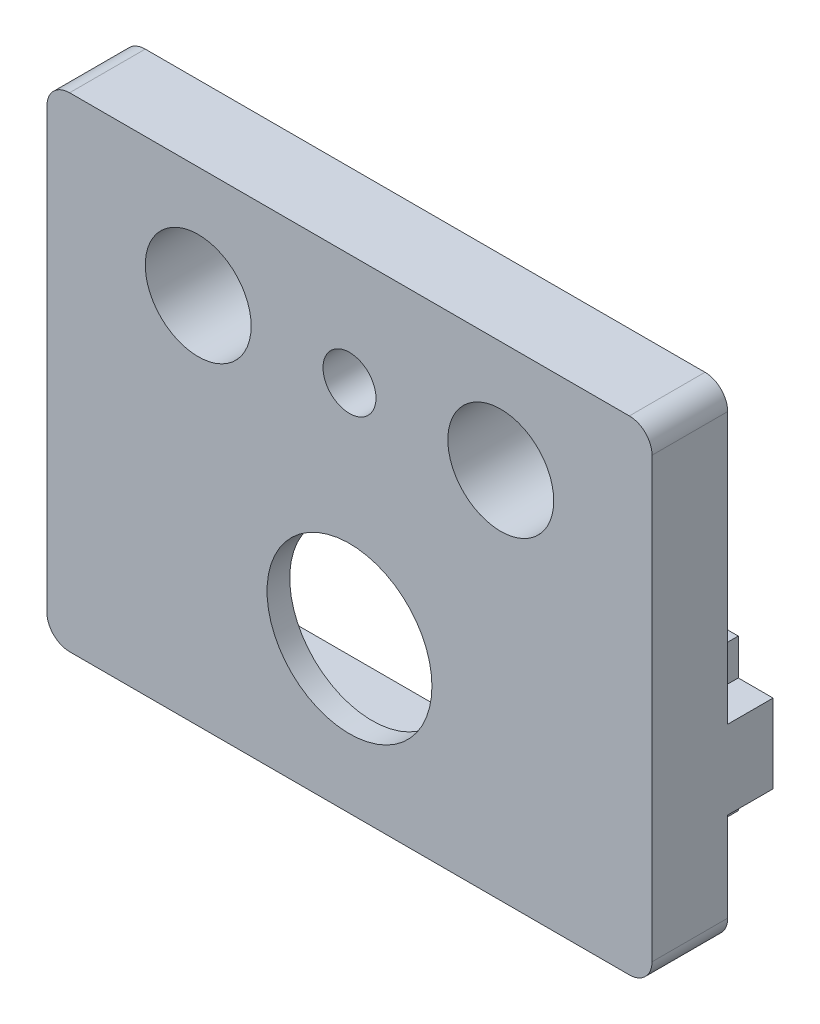
SolidWorks part; units mm, degrees
ref_plane "前视基准面" through (0, 0, 0) normal (0, 0, 1) x (1, 0, 0)
ref_plane "上视基准面" through (0, 0, 0) normal (0, 1, 0) x (1, 0, 0)
ref_plane "右视基准面" through (0, 0, 0) normal (1, 0, 0) x (0, 0, -1)
sketch "草图1" plane through (0, 0, 0) normal (0, 0, 1) x (1, 0, 0)
  line L1 (-9.5, -5.75) -> (9.5, -5.75)
  line L3 (-9.5, 5.75) -> (9.5, 5.75)
  line L5 (-20, -10) -> (20, -10)
  line L6 (-20, -10) -> (-20, 10)
  line L11 (-20, 10) -> (20, 10)
  line L12 (20, -10) -> (20, 10)
  line L13 (-20, -10) -> (20, 10) construction
  line L14 (-20, 10) -> (20, -10) construction
  arc A0 (9.5, -5.75) -> (9.5, 5.75) centre (-0.7708, 0) ccw
  arc A1 (-9.5, -5.75) -> (-9.5, 5.75) centre (0.7708, 0) cw
  point P0 (0, 0)
  point P6 (0, 0)
  point P7 (0, 0)
extrude "凸台-拉伸1" add sketch "草图1" along normal blind 3.5
sketch "草图2" plane through (0, 0, 3.5) normal (0, 0, 1) x (1, 0, 0)
  line L4 (20, -10) -> (20, 10)
  line L5 (20, 10) -> (-20, 10)
  line L6 (-20, 10) -> (-20, -10)
  line L7 (-20, -10) -> (20, -10)
  line L8 (20, -10) -> (20, 10)
  line L9 (20, 10) -> (-20, 10)
  line L10 (-20, 10) -> (-20, -10)
  line L11 (-20, -10) -> (20, -10)
  circle A0 centre (0, 0) radius 5.25
  dimension "D1" = 0
extrude "凸台-拉伸2" add sketch "草图2" along normal blind 1.5
sketch "草图3" plane through (0, 0, 5) normal (0, 0, 1) x (1, 0, 0)
  line L9 (-16.5607, 5.5) -> (-18.2, 5.5)
  line L13 (-13.9, -2.8393) -> (-13.9, 2.8393)
  line L19 (-16.5607, 5.5) -> (-13.9, 2.8393)
  line L22 (-18.2, 3.1) -> (-18.2, 5.5)
  line L23 (-18.2, 3.1) -> (-20, 3.1)
  line L24 (-18.2, -3.1) -> (-20, -3.1)
  line L25 (-18.2, -3.1) -> (-18.2, -5.5)
  line L28 (-16.5607, -5.5) -> (-13.9, -2.8393)
  line L32 (-16.5607, -5.5) -> (-18.2, -5.5)
  line L41 (18.2, 3.1) -> (20, 3.1)
  line L45 (18.2, 3.1) -> (18.2, 5.5)
  line L48 (16.5607, 5.5) -> (13.9, 2.8393)
  line L54 (13.9, -2.8393) -> (13.9, 2.8393)
  line L56 (16.5607, 5.5) -> (18.2, 5.5)
  line L63 (16.5607, -5.5) -> (18.2, -5.5)
  line L67 (16.5607, -5.5) -> (13.9, -2.8393)
  line L70 (18.2, -3.1) -> (18.2, -5.5)
  line L74 (18.2, -3.1) -> (20, -3.1)
  line L88 (-20, 3.1) -> (-20, -3.1)
  line L90 (20, 3.1) -> (20, -3.1)
  point P0 (-10, 0)
  point P8 (-10, 8.2)
  point P9 (-9.8043, 8.2)
  point P13 (-10, 8.2)
  point P20 (-5, 5)
  point P33 (-15, 5)
  point P50 (-15, -5)
  point P51 (-5, -5)
  point P52 (-10, -8.2)
  point P53 (-9.8043, -8.2)
  point P54 (10, 0)
  point P58 (10, 8.2)
  point P59 (10.1957, 8.2)
  point P63 (10, 8.2)
  point P70 (15, 5)
  point P83 (5, 5)
  point P102 (5, -5)
  point P103 (15, -5)
  point P104 (10, -8.2)
  point P105 (10.1957, -8.2)
extrude "凸台-拉伸3" add sketch "草图3" against normal blind 8
sketch "草图4" plane through (0, 0, 5) normal (0, 0, 1) x (1, 0, 0)
  line L3 (-20, 10) -> (-20, -10) construction
  line L6 (20, 10) -> (-20, 10)
  line L8 (-20, 10) -> (-20, 22)
  line L9 (-20, 22) -> (20, 22)
  line L10 (20, 22) -> (20, 10)
  circle A2 centre (-10, 14.64) radius 3.5
  circle A3 centre (10, 14.64) radius 3.5
extrude "凸台-拉伸4" add sketch "草图4" against normal blind 5
fillet "圆角1" radius 1.5 4 edges at (-20, 22, 2.5) (20, 22, 2.5) (20, -10, 2.5) (-20, -10, 2.5)
sketch "草图5" plane through (0, 0, 5) normal (0, 0, 1) x (1, 0, 0)
  circle A0 centre (0, 14.64) radius 1.75
extrude "切除-拉伸1" cut sketch "草图5" against normal blind 5
sketch "草图6" plane through (0, 0, -3) normal (0, 0, -1) x (-1, 0, 0)
  line L0 (-18.2, 5.5) -> (-18.2, 3.1) construction
  line L1 (-18.2, 3.1) -> (-20, 3.1) construction
  line L2 (-20, 3.1) -> (-20, -3.1) construction
  line L3 (-20, -3.1) -> (-18.2, -3.1) construction
  line L4 (-18.2, -3.1) -> (-18.2, -5.5) construction
  line L5 (-18.2, -5.5) -> (-16.5607, -5.5) construction
  line L6 (-16.5607, -5.5) -> (-13.9, -2.8393) construction
  line L7 (-13.9, -2.8393) -> (-13.9, 2.8393) construction
  line L8 (-13.9, 2.8393) -> (-16.5607, 5.5) construction
  line L9 (-16.5607, 5.5) -> (-18.2, 5.5) construction
  line L10 (18.2, -5.5) -> (18.2, -3.1) construction
  line L11 (18.2, -3.1) -> (20, -3.1) construction
  line L12 (20, -3.1) -> (20, 3.1) construction
  line L13 (20, 3.1) -> (18.2, 3.1) construction
  line L14 (18.2, 3.1) -> (18.2, 5.5) construction
  line L15 (18.2, 5.5) -> (16.5607, 5.5) construction
  line L16 (16.5607, 5.5) -> (13.9, 2.8393) construction
  line L17 (13.9, 2.8393) -> (13.9, -2.8393) construction
  line L18 (13.9, -2.8393) -> (16.5607, -5.5) construction
  line L19 (16.5607, -5.5) -> (18.2, -5.5) construction
  line L20 (-18.2, 5.5) -> (-18.2, 3.1)
  line L21 (-18.2, 3.1) -> (-20, 3.1)
  line L22 (-20, 3.1) -> (-20, 2.6)
  line L23 (-20, -3.1) -> (-18.2, -3.1)
  line L24 (-18.2, -3.1) -> (-18.2, -5.5)
  line L25 (-18.2, -5.5) -> (-16.5607, -5.5)
  line L26 (-16.5607, -5.5) -> (-13.9, -2.8393)
  line L27 (-13.9, -2.8393) -> (-13.9, 2.8393)
  line L28 (-13.9, 2.8393) -> (-16.5607, 5.5)
  line L29 (-16.5607, 5.5) -> (-18.2, 5.5)
  line L30 (18.2, -5.5) -> (18.2, -3.1)
  line L31 (18.2, -3.1) -> (20, -3.1)
  line L32 (20, -3.1) -> (20, -2.6)
  line L33 (20, 3.1) -> (18.2, 3.1)
  line L34 (18.2, 3.1) -> (18.2, 5.5)
  line L35 (18.2, 5.5) -> (16.5607, 5.5)
  line L36 (16.5607, 5.5) -> (13.9, 2.8393)
  line L37 (13.9, 2.8393) -> (13.9, -2.8393)
  line L38 (13.9, -2.8393) -> (16.5607, -5.5)
  line L39 (16.5607, -5.5) -> (18.2, -5.5)
  line L40 (-20, -2.6) -> (-20, -3.1)
  line L41 (19.5, -2.6) -> (20, -2.6)
  line L42 (19.5, 2.6) -> (20, 2.6)
  line L43 (20, 2.6) -> (20, 3.1)
  line L70 (-17.7, 5) -> (-17.7, 2.6)
  line L71 (-17.7, 2.6) -> (-19.5, 2.6)
  line L72 (-19.5, 2.6) -> (-19.5, -2.6)
  line L73 (-19.5, -2.6) -> (-17.7, -2.6)
  line L74 (-17.7, -2.6) -> (-17.7, -5)
  line L75 (-17.7, -5) -> (-16.7678, -5)
  line L76 (-16.7678, -5) -> (-14.4, -2.6322)
  line L77 (-14.4, -2.6322) -> (-14.4, 2.6322)
  line L78 (-14.4, 2.6322) -> (-16.7678, 5)
  line L79 (-16.7678, 5) -> (-17.7, 5)
  line L80 (-17.7, 5) -> (-17.7, 2.6)
  line L81 (-17.7, 2.6) -> (-19.5, 2.6)
  line L83 (-19.5, -2.6) -> (-17.7, -2.6)
  line L84 (-17.7, -2.6) -> (-17.7, -5)
  line L85 (-17.7, -5) -> (-16.7678, -5)
  line L86 (-16.7678, -5) -> (-14.4, -2.6322)
  line L87 (-14.4, -2.6322) -> (-14.4, 2.6322)
  line L88 (-14.4, 2.6322) -> (-16.7678, 5)
  line L89 (-16.7678, 5) -> (-17.7, 5)
  line L90 (-19.5, -2.6) -> (-20, -2.6)
  line L91 (-19.5, 2.6) -> (-20, 2.6)
  line L100 (17.7, -5) -> (17.7, -2.6)
  line L101 (17.7, -2.6) -> (19.5, -2.6)
  line L102 (19.5, -2.6) -> (19.5, 2.6)
  line L103 (19.5, 2.6) -> (17.7, 2.6)
  line L104 (17.7, 2.6) -> (17.7, 5)
  line L105 (17.7, 5) -> (16.7678, 5)
  line L106 (16.7678, 5) -> (14.4, 2.6322)
  line L107 (14.4, 2.6322) -> (14.4, -2.6322)
  line L108 (14.4, -2.6322) -> (16.7678, -5)
  line L109 (16.7678, -5) -> (17.7, -5)
  line L110 (17.7, -5) -> (17.7, -2.6)
  line L111 (17.7, -2.6) -> (19.5, -2.6)
  line L113 (19.5, 2.6) -> (17.7, 2.6)
  line L114 (17.7, 2.6) -> (17.7, 5)
  line L115 (17.7, 5) -> (16.7678, 5)
  line L116 (16.7678, 5) -> (14.4, 2.6322)
  line L117 (14.4, 2.6322) -> (14.4, -2.6322)
  line L118 (14.4, -2.6322) -> (16.7678, -5)
  line L119 (16.7678, -5) -> (17.7, -5)
  dimension "D1" = 0.5
  dimension "D2" = 0.5
extrude "切除-拉伸2" cut sketch "草图6" against normal blind 3
sketch "草图7" plane through (0, 0, 0) normal (0, 0, -1) x (-1, 0, 0)
  line L4 (9.6166, 5.95) -> (-9.6166, 5.95)
  line L5 (-9.6166, -5.95) -> (9.6166, -5.95)
  line L6 (9.6166, 5.95) -> (-9.6166, 5.95)
  line L7 (-9.6166, -5.95) -> (9.6166, -5.95)
  arc A4 (9.6166, -5.95) -> (9.6166, 5.95) centre (-0.7708, 0) ccw
  arc A5 (-9.6166, 5.95) -> (-9.6166, -5.95) centre (0.7708, 0) ccw
  arc A6 (9.6166, -5.95) -> (9.6166, 5.95) centre (-0.7708, 0) ccw
  arc A7 (-9.6166, 5.95) -> (-9.6166, -5.95) centre (0.7708, 0) ccw
  dimension "D1" = 0.2
extrude "切除-拉伸3" cut sketch "草图7" against normal blind 3.5
sketch "草图8" plane through (0, 0, 5) normal (0, 0, 1) x (1, 0, 0)
  circle A0 centre (0, 0) radius 5.25 construction
  circle A1 centre (0, 0) radius 5.25
  circle A2 centre (0, 0) radius 5.45
  dimension "D1" = 0.2
extrude "切除-拉伸4" cut sketch "草图8" against normal blind 3.5
